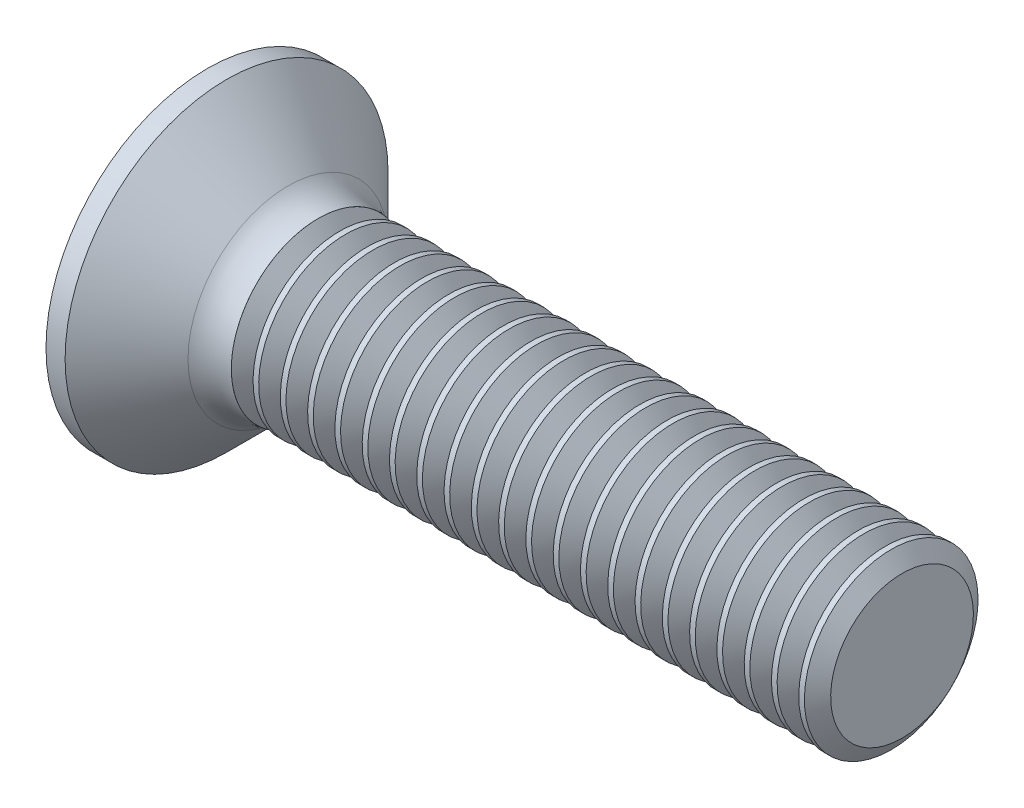
SolidWorks part; units mm, degrees
revolve "Base-Revolve" add sketch "BodySke"
sketch "BodySke" plane through (0, 0, 0) normal (0, 0, 1) x (1, 0, 0)
  line L0 (0, 0) -> (0, 4.65)
  line L1 (0, 4.65) -> (0.55, 4.65)
  line L2 (2.7, 2.5) -> (20, 2.5)
  line L3 (20, 2.5) -> (20, 0)
  line L4 (20, 0) -> (0, 0)
  line L5 (-6.35, 0) -> (82.55, 0) construction
  line L6 (2.7, -2.5) -> (20, -2.5) construction
  line L7 (0.55, -4.65) -> (2.7, -2.5) construction
  line L8 (0.55, 4.65) -> (2.7, 2.5)
  line L9 (0, -4.65) -> (0.55, -4.65) construction
  line L10 (3.5, 4.0875) -> (3.5, -5.4375) construction
  line L11 (0, 6.35) -> (0, -3.175) construction
  dimension "Head_ang" = 90
cosmetic thread "ThreadCosmetic" [suppressed]
fillet "Fillet1" radius 1.3 1 edges at (2.7, 0, 2.5)
ref_plane "Plane1" through (0, 0, 0) normal (0, 0, 1) x (1, 0, 0)
ref_plane "Plane2" through (0, 0, 0) normal (0, 1, 0) x (1, 0, 0)
ref_plane "Plane3" through (0, 0, 0) normal (1, 0, 0) x (0, 0, -1)
sketch "Sketch3" plane through (0, 0, 0) normal (-1, 0, 0) x (0, 0, 1)
  line L0 (-0.515, 2.45) -> (0.515, 2.45)
  line L1 (0.515, 2.45) -> (0.515, -2.45)
  line L2 (0.515, -2.45) -> (-0.515, -2.45)
  line L3 (-0.515, -2.45) -> (-0.515, 2.45)
  dimension "D1" = 1.4
  dimension "D2" = 0.37
ref_plane "Plane4" through (3.05, 0, 0) normal (-1, 0, 0) x (0, 0, 1)
sketch "Sketch4" plane through (3.05, 0, 0) normal (-1, 0, 0) x (0, 0, 1)
  line L0 (-0.515, 0.9293) -> (0.515, 0.9293)
  line L3 (0.515, 0.9293) -> (0.515, -0.9293)
  line L4 (0.515, -0.9293) -> (-0.515, -0.9293)
  line L5 (-0.515, -0.9293) -> (-0.515, 0.9293)
  dimension "D2" = 1.0749
  dimension "D1" = 0.74
  dimension "D4" = 0.5375
  dimension "D3" = 0.37
loft "Recess" cut profiles "Sketch3", "Sketch4"
pattern_circular "RecPat" count 2 every 90 about axis through (0, 0, 0) along (1, 0, 0) of "Recess"
sketch "RecCorSke" plane through (0, 0, 0) normal (0, 0, 1) x (1, 0, 0)
  line L0 (-3.175, 0) -> (15.875, 0) construction
  line L2 (0, 0) -> (0, 1.0643)
  line L3 (0, 1.0643) -> (3.05, 0.851)
  line L4 (3.05, 0.851) -> (3.3265, 0)
  line L5 (3.3265, 0) -> (0, 0)
  dimension "Depth" = 1.73
  dimension "Draft_angle" = 4
  dimension "Bottom_angle" = 18
revolve "RecessCore" cut sketch "RecCorSke" angle 360 about L0
sketch "ThdSchSke" plane through (0, 0, 0) normal (0, 0, 1) x (1, 0, 0)
  line L0 (3.5, -2.055) -> (3.1884, -2.5)
  line L1 (3.5, -2.055) -> (3.8116, -2.5)
  line L2 (3.8116, -2.5) -> (3.8116, -3.125)
  line L3 (-3.175, 0) -> (5.1513, 0) construction
  line L5 (3.8116, -3.125) -> (3.1884, -3.125)
  line L6 (3.1884, -3.125) -> (3.1884, -2.5)
  line L7 (0, 4.65) -> (0, -4.65) construction
  dimension "Thread_minor" = 1.993
  dimension "Diameter" = 2.5
  dimension "Start" = 1.95
revolve "ThreadSchematic" cut sketch "ThdSchSke" angle 360 about L3
pattern_linear "ThdSchPat" count 22 spacing 0.7857 along (1, 0, 0) of "ThreadSchematic"
equation "\"D1@Sketch3\" = \"Cross_dia@Sketch3\" / 2"
equation "\"D2@Sketch3\" = \"Cross_width@Sketch3\" / 2"
equation "\"Depth@RecCorSke\" = \"Cross_depth@Plane4\""
equation "\"D1@Sketch4\" = \"Cross_width@Sketch3\""
equation "\"D2@Sketch4\" = \"Cross_dia@Sketch3\" - 2.0 * \"Cross_depth@Plane4\" * tan(26.5  * 0.017453292)"
equation "\"D3@Sketch4\" = \"D1@Sketch4\" / 2"
equation "\"D4@Sketch4\" = \"D2@Sketch4\" / 2"
equation "\"Thread_length@ThreadCosmetic\" = ((sgn( (\"Length@BodySke\" - \"Advance@BodySke\" * 1.0 - \"Head_ht@BodySke\" ) - \"Thread_nom@BodySke\" )-1)*( (\"Length@BodySke\" - \"Advance@BodySke\" * 1.0 - \"Head_ht@BodySke\" ) - \"Thread_nom@BodySke\" ))/-2+ \"Thread_nom@BodySke\""
equation "\"Thread_minor@ThdSchSke\" = \"Thread_minor@ThreadCosmetic\""
equation "\"Diameter@ThdSchSke\" = \"Diameter@BodySke\""
equation "\"Overcut@ThdSchSke\" = \"Diameter@BodySke\" * 1.25"
equation "\"Start@ThdSchSke\" = 0.000001 + \"Length@BodySke\" - \"Thread_length@ThreadCosmetic\"  '---Countersunk---"
equation "\"Num_threads@ThdSchPat\" = int( \"Thread_length@ThreadCosmetic\" / \"Advance@BodySke\" + 0.999 )  + 1"
equation "\"Advance@ThdSchPat\" = \"Thread_length@ThreadCosmetic\" /  (\"Num_threads@ThdSchPat\" - 1) 'relax it"
